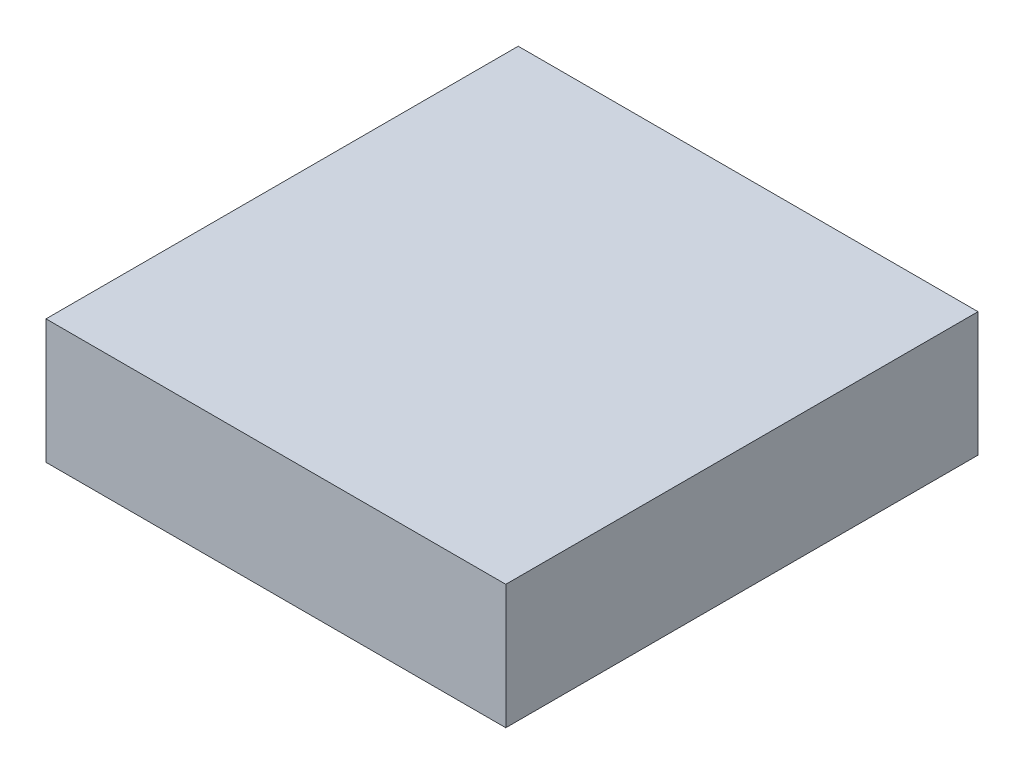
SolidWorks part; units mm, degrees
material "1060 Alloy"
ref_plane "Front Plane" through (0, 0, 0) normal (0, 0, 1) x (1, 0, 0)
ref_plane "Top Plane" through (0, 0, 0) normal (0, 1, 0) x (1, 0, 0)
ref_plane "Right Plane" through (0, 0, 0) normal (1, 0, 0) x (0, 0, -1)
sketch "Sketch1" plane through (0, 0, 0) normal (0, 1, 0) x (1, 0, 0)
  line L1 (-18.5, 19) -> (18.5, 19)
  line L2 (-18.5, 19) -> (-18.5, 3)
  line L3 (-18.5, -19) -> (18.5, -19)
  line L4 (18.5, 19) -> (18.5, -19)
  line L5 (-18.5, 19) -> (18.5, -19) construction
  line L6 (-18.5, -19) -> (18.5, 19) construction
  line L8 (-18.5, -3) -> (-18.5, -19)
  line L9 (-18.5, 3) -> (-18.5, -3)
  point P0 (0, 0)
  dimension "D1" = 37
  dimension "D2" = 38
extrude "Boss-Extrude1" add sketch "Sketch1" along normal blind 10
sketch "Sketch2" plane through (0, 10, 0) normal (0, 1, 0) x (1, 0, 0)
  line L0 (18.5, -19) -> (18.5, 19) construction
  line L1 (-18.5, 19) -> (18.5, 19)
  line L2 (-18.5, 19) -> (-18.5, 17)
  line L3 (-18.5, 17) -> (18.5, 17)
  line L4 (18.5, 19) -> (18.5, 17)
  line L6 (-18.5, -19) -> (18.5, -19)
  line L7 (-18.5, -19) -> (-18.5, -16.9983)
  line L8 (-18.5, -16.9983) -> (18.5, -16.9983)
  line L9 (18.5, -19) -> (18.5, -16.9983)
  dimension "D1" = 2
  dimension "D2" = 2.0017
extrude "Boss-Extrude2" [suppressed] add sketch "Sketch2" along normal blind 8
fillet "Fillet1" [suppressed] radius 2
fillet "Fillet2" [suppressed] radius 0.25
hole_wizard "Tap Drill for M2.5 Tap1" [suppressed] positions "Sketch3" profile "Sketch4" hole size "M2.5" standard "ISO"
sketch "Sketch3" [suppressed] plane through (0, 2, 0) normal (0, 1, 0) x (1, 0, 0)
  line L0 (-18.5, 16.75) -> (-18.5, 3) construction
  line L1 (-18.5, 17) -> (18.5, 17) construction
  line L2 (-18.5, -3) -> (-18.5, -16.7483) construction
  line L3 (-16.5, -19) -> (16.5, -19) construction
  line L4 (16.5, 19) -> (-16.5, 19) construction
  line L5 (18.5, -16.7483) -> (18.5, 16.75) construction
  point P0 (-13.5, 13)
  point P2 (14.5, 13)
  point P4 (14.5, -13)
  point P6 (-13.5, -13)
  dimension "D1" = 5
  dimension "D2" = 4
  dimension "D3" = 5
  dimension "D4" = 6
  dimension "D5" = 6
  dimension "D6" = 6
  dimension "D7" = 4
  dimension "D8" = 4
sketch "Sketch4" plane through (-13.5, 2, -13) normal (1, 0, 0) x (0, 0, 1)
  line L0 (0, 0) -> (0, 2)
  line L1 (0, 2) -> (1.025, 2)
  line L2 (1.025, 2) -> (1.025, 0)
  line L5 (1.025, 0) -> (0, 0)
  line L11 (0, -6.35) -> (0, 107.95) construction
  dimension "Thru Hole Dia." = 2.05
  dimension "Thru Hole Depth" = 2
sketch "Sketch5" plane through (0, 10, 0) normal (0, 1, 0) x (1, 0, 0)
  line L0 (18.5, -19) -> (18.5, 19) construction
  circle A0 centre (3.5, 0) radius 5
  dimension "D1" = 10
  dimension "D2" = 15
extrude "Cut-Extrude1" [suppressed] cut sketch "Sketch5" against normal through all
sketch "Sketch8" [suppressed] plane through (0, 2, 0) normal (0, 1, 0) x (1, 0, 0)
  circle A0 centre (3.5, 0) radius 11 construction
  dimension "D1" = 22
hole_wizard "M2.5 Clearance Hole1" [suppressed] positions "Sketch11" profile "Sketch12" hole size "M2.5" standard "ISO"
sketch "Sketch11" [suppressed] plane through (0, 2, 0) normal (0, 1, 0) x (1, 0, 0)
  circle A0 centre (3.5, 0) radius 11 construction
  point P0 (3.5, 11)
sketch "Sketch12" plane through (3.5, 2, -11) normal (1, 0, 0) x (0, 0, 1)
  line L0 (0, 0) -> (0, 2.001)
  line L1 (0, 2.001) -> (1.45, 2.001)
  line L2 (1.45, 2.001) -> (1.45, 0)
  line L5 (1.45, 0) -> (0, 0)
  line L11 (0, -6.35) -> (0, 107.95) construction
  dimension "Thru Hole Dia." = 2.9
  dimension "Thru Hole Depth" = 2.001
pattern_circular "CirPattern1" [suppressed] count 8 over 360
hole_wizard "M2.5 Clearance Hole2" [suppressed] positions "Sketch13" profile "Sketch14" hole size "M2.5" standard "ISO"
sketch "Sketch13" [suppressed] plane through (0, 0, 19) normal (0, 0, 1) x (1, 0, 0)
  line L0 (-18.5, 8) -> (-18.5, 2) construction
  line L1 (18.5, 8) -> (18.5, 2.25) construction
  point P0 (-14.5, 5.8701)
  point P2 (-7.5, 5.8701)
  point P4 (7.5, 5.8701)
  point P6 (14.5, 5.8701)
  dimension "D1" = 4
  dimension "D2" = 4
  dimension "D3" = 7
  dimension "D4" = 7
  dimension "D5" = 22
sketch "Sketch14" plane through (-14.5, 5.8701, 19) normal (1, 0, 0) x (0, -1, 0)
  line L0 (0, 0) -> (0, 38)
  line L1 (0, 38) -> (1.45, 38)
  line L2 (1.45, 38) -> (1.45, 0)
  line L5 (1.45, 0) -> (0, 0)
  line L11 (0, -6.35) -> (0, 107.95) construction
  dimension "Thru Hole Dia." = 2.9
  dimension "Thru Hole Depth" = 38
